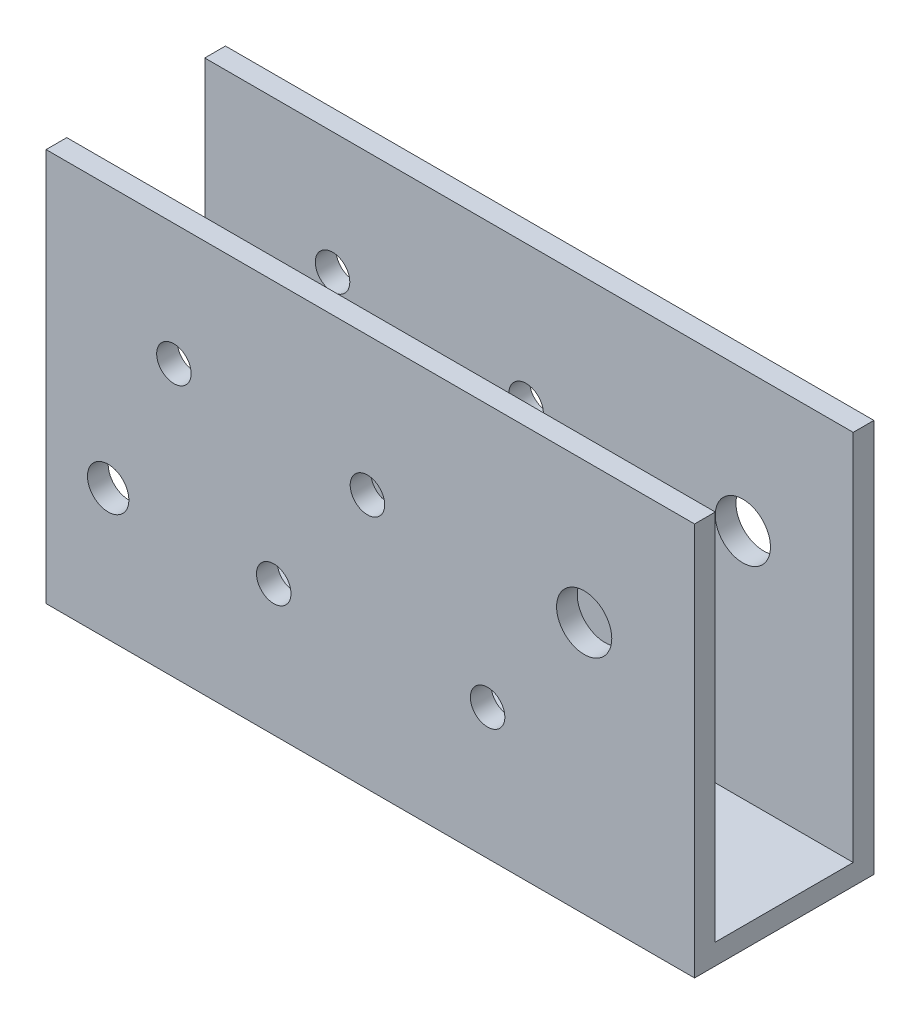
SolidWorks part; units mm, degrees
ref_plane "정면" through (0, 0, 0) normal (0, 0, 1) x (1, 0, 0)
ref_plane "윗면" through (0, 0, 0) normal (0, 1, 0) x (1, 0, 0)
ref_plane "우측면" through (0, 0, 0) normal (1, 0, 0) x (0, 0, -1)
sketch "스케치1" plane through (0, 0, 0) normal (0, 1, 0) x (1, 0, 0)
  line L1 (-47, -13) -> (47, -13)
  line L2 (-47, -13) -> (-47, 13)
  line L3 (-47, 13) -> (47, 13)
  line L4 (47, -13) -> (47, 13)
  line L5 (-47, -13) -> (47, 13) construction
  line L6 (-47, 13) -> (47, -13) construction
  point P0 (0, 0)
  dimension "D1" = 94
  dimension "D2" = 26
extrude "보스-돌출1" add sketch "스케치1" along normal blind 3
sketch "스케치2" plane through (0, 3, 0) normal (0, 1, 0) x (1, 0, 0)
  line L1 (-47, -10) -> (47, -10)
  line L2 (-47, -10) -> (-47, 10)
  line L3 (-47, 10) -> (47, 10)
  line L4 (47, -10) -> (47, 10)
  line L5 (-47, -10) -> (47, 10) construction
  line L6 (-47, 10) -> (47, -10) construction
  line L7 (47, -13) -> (-47, -13)
  line L8 (47, -13) -> (47, 13)
  line L9 (47, 13) -> (-47, 13)
  line L10 (-47, -13) -> (-47, 13)
  line L11 (47, -13) -> (-47, 13) construction
  line L12 (47, 13) -> (-47, -13) construction
  point P0 (0, 0)
  point P6 (0, 0)
  line M3 (47, -13) -> (47, 13)
  line M4 (47, 13) -> (-47, 13)
  line M5 (-47, 13) -> (-47, -13)
  line M6 (-47, -13) -> (47, -13)
  dimension "D1" = 94
  dimension "D2" = 20
extrude "보스-돌출2" add sketch "스케치2" along normal blind 54 contours L3 M5 M3 M4 | L1 M5 M6 M3
sketch "스케치3" plane through (0, 0, 13) normal (0, 0, 1) x (1, 0, 0)
  line L0 (-47, 2) -> (47, 2)
  line L1 (-47, 57) -> (-47, 0) construction
  line L2 (47, 57) -> (47, 0) construction
  line L3 (-47, 0) -> (47, 0) construction
  line L4 (-47, 2) -> (-38, 2)
  line L5 (-38, 2) -> (-38, 19)
  line L6 (-38, 19) -> (-14, 19)
  line L7 (-14, 19) -> (17, 19)
  circle A0 centre (-38, 19) radius 3
  circle A1 centre (-14, 19) radius 2.5
  circle A2 centre (17, 19) radius 2.5
  circle A3 centre (-28.474, 39.3839) radius 2.5
  circle A4 centre (-0.4153, 36.9362) radius 2.5
  circle A5 centre (31, 36.6139) radius 4
  dimension "D4" = 6
  dimension "D7" = 5
  dimension "D8" = 5
  dimension "D11" = 5
  dimension "D14" = 5
  dimension "D17" = 8
  dimension "D1" = 2
  dimension "D2" = 9
  dimension "D3" = 17
  dimension "D5" = 24
  dimension "D6" = 31
  dimension "D9" = 22.5
  dimension "D10" = 25
  dimension "D12" = 22.5
  dimension "D13" = 25
  dimension "D15" = 22.5
  dimension "D16" = 69
extrude "컷-돌출1" cut sketch "스케치3" against normal through all
